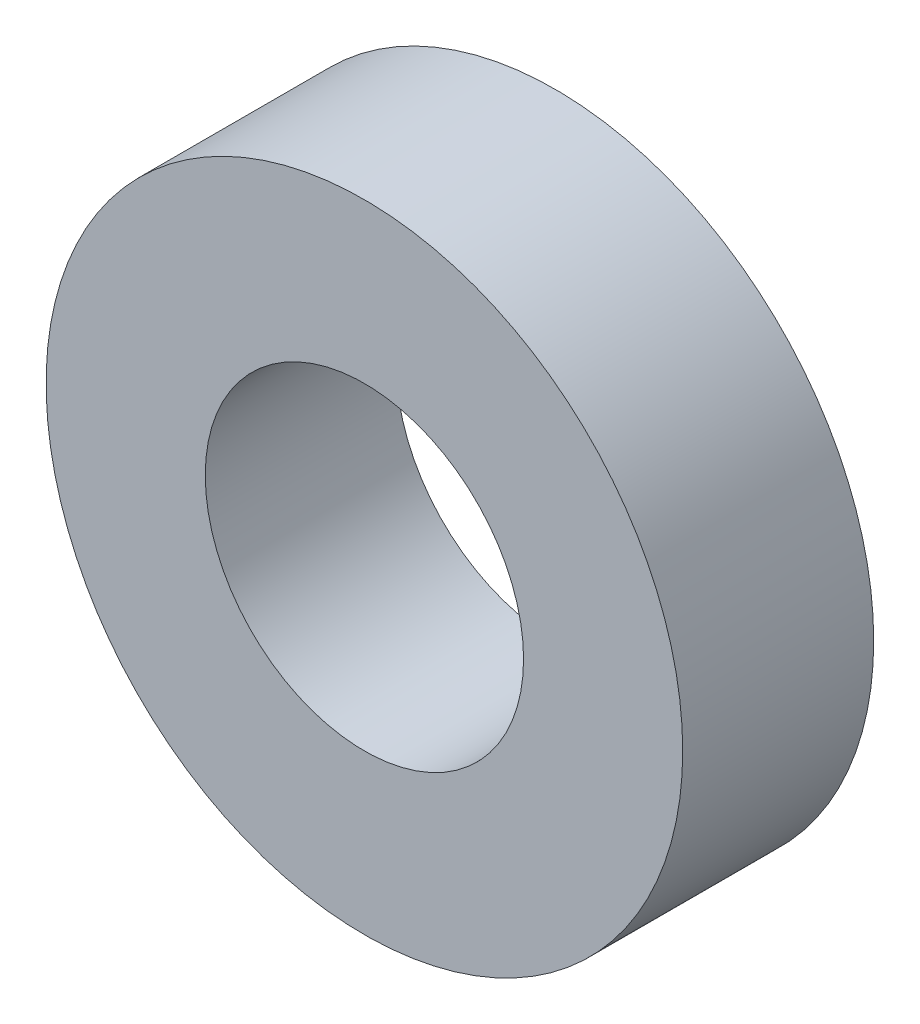
SolidWorks part; units mm, degrees
other "Thermal 1"
ref_plane "Front Plane" through (0, 0, 0) normal (0, 0, 1) x (1, 0, 0)
ref_plane "Top Plane" through (0, 0, 0) normal (0, 1, 0) x (1, 0, 0)
ref_plane "Right Plane" through (0, 0, 0) normal (1, 0, 0) x (0, 0, -1)
sketch "Sketch1" plane through (0, 0, 0) normal (0, 0, 1) x (1, 0, 0)
  circle A0 centre (0, 0) radius 50
  circle A1 centre (0, 0) radius 25
  dimension "D1" = 50
  dimension "D2" = 100
extrude "Boss-Extrude1" add sketch "Sketch1" along normal blind 30
